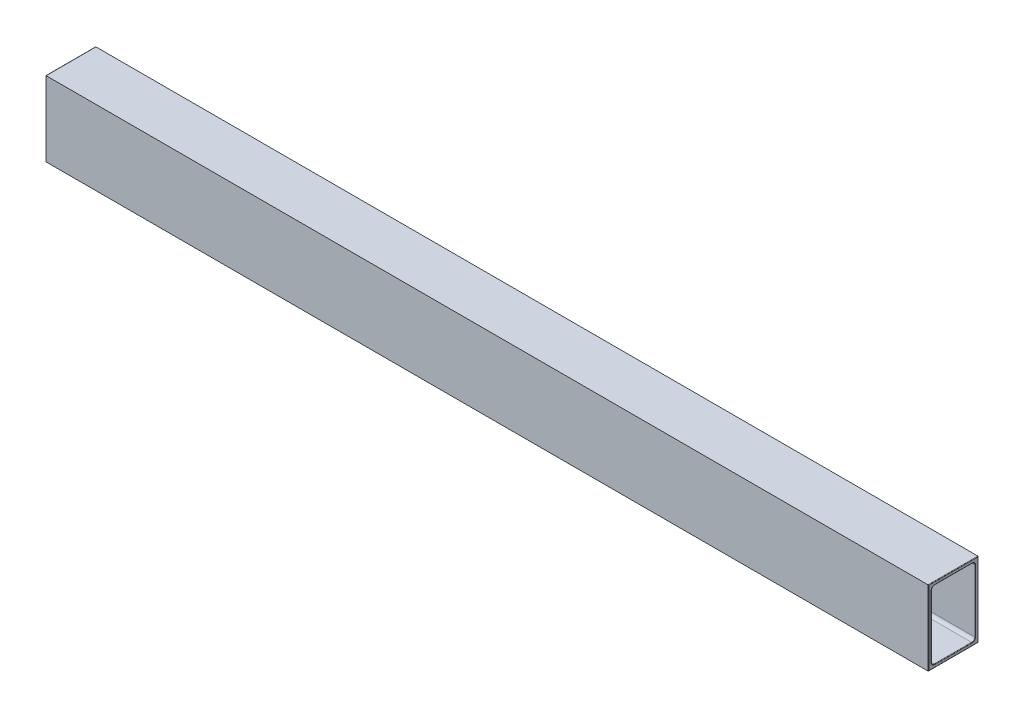
SolidWorks part; units mm, degrees
material "ASTM A500 Grade B Steel"
ref_plane "Front Plane" through (0, 0, 0) normal (0, 0, 1) x (1, 0, 0)
ref_plane "Top Plane" through (0, 0, 0) normal (0, 1, 0) x (1, 0, 0)
ref_plane "Right Plane" through (0, 0, 0) normal (1, 0, 0) x (0, 0, -1)
sketch "Sketch1" plane through (0, 0, 0) normal (1, 0, 0) x (0, 0, -1)
  line L0 (-95.25, 12.7) -> (-95.25, 139.7)
  line L1 (0, 0) -> (-101.6, 0)
  line L2 (0, 0) -> (0, 152.4)
  line L3 (0, 152.4) -> (-101.6, 152.4)
  line L4 (-101.6, 0) -> (-101.6, 152.4)
  line L5 (-12.7, 146.05) -> (-88.9, 146.05)
  line L6 (-6.35, 12.7) -> (-6.35, 139.7)
  line L7 (-12.7, 6.35) -> (-88.9, 6.35)
  line L8 (-95.25, 6.35) -> (-95.25, 146.05) construction
  line L9 (-6.35, 6.35) -> (-95.25, 6.35) construction
  line L10 (-6.35, 6.35) -> (-6.35, 146.05) construction
  line L11 (-6.35, 146.05) -> (-95.25, 146.05) construction
  arc A0 (-95.25, 12.7) -> (-88.9, 6.35) centre (-88.9, 12.7) ccw
  arc A1 (-6.35, 12.7) -> (-12.7, 6.35) centre (-12.7, 12.7) cw
  arc A2 (-12.7, 146.05) -> (-6.35, 139.7) centre (-12.7, 139.7) cw
  arc A3 (-95.25, 139.7) -> (-88.9, 146.05) centre (-88.9, 139.7) cw
  dimension "D4" = 6.35
  dimension "D1" = 152.4
  dimension "D2" = 101.6
  dimension "D3" = 6.35
extrude "Boss-Extrude1" add sketch "Sketch1" along normal blind 1800
fillet "Fillet1" radius 1 24 edges at (0, 152.4, 50.8) (1800, 8.2099, 8.2099) (1800, 76.2, 6.35) (1800, 144.1901, 8.2099) (1800, 146.05, 50.8) (1800, 144.1901, 93.3901) (1800, 76.2, 95.25) (1800, 8.2099, 93.3901) (1800, 6.35, 50.8) (1800, 0, 50.8) (1800, 76.2, 101.6) (1800, 152.4, 50.8) (1800, 76.2, 0) (0, 76.2, 95.25) (0, 144.1901, 93.3901) (0, 146.05, 50.8) (0, 144.1901, 8.2099) (0, 76.2, 6.35) (0, 8.2099, 8.2099) (0, 6.35, 50.8) (0, 8.2099, 93.3901) (0, 76.2, 101.6) (0, 0, 50.8) (0, 76.2, 0)
sketch "Sketch2" plane through (0, 0, 0) normal (0, -1, 0) x (1, 0, 0)
  line L0 (1799, 101.6) -> (1, 101.6) construction
  line L1 (747.6, 101.6) -> (1052.4, 101.6)
  line L2 (747.6, 101.6) -> (747.6, 0)
  line L3 (747.6, 0) -> (1052.4, 0)
  line L4 (1052.4, 101.6) -> (1052.4, 0)
  line L5 (1799, 0) -> (1, 0) construction
  point P8 (900, 101.6)
  point P9 (900, 101.6)
  dimension "D1" = 304.8
split line "Split Line1"
equation "\"D4@Sketch1\"=\"D3@Sketch1\""
